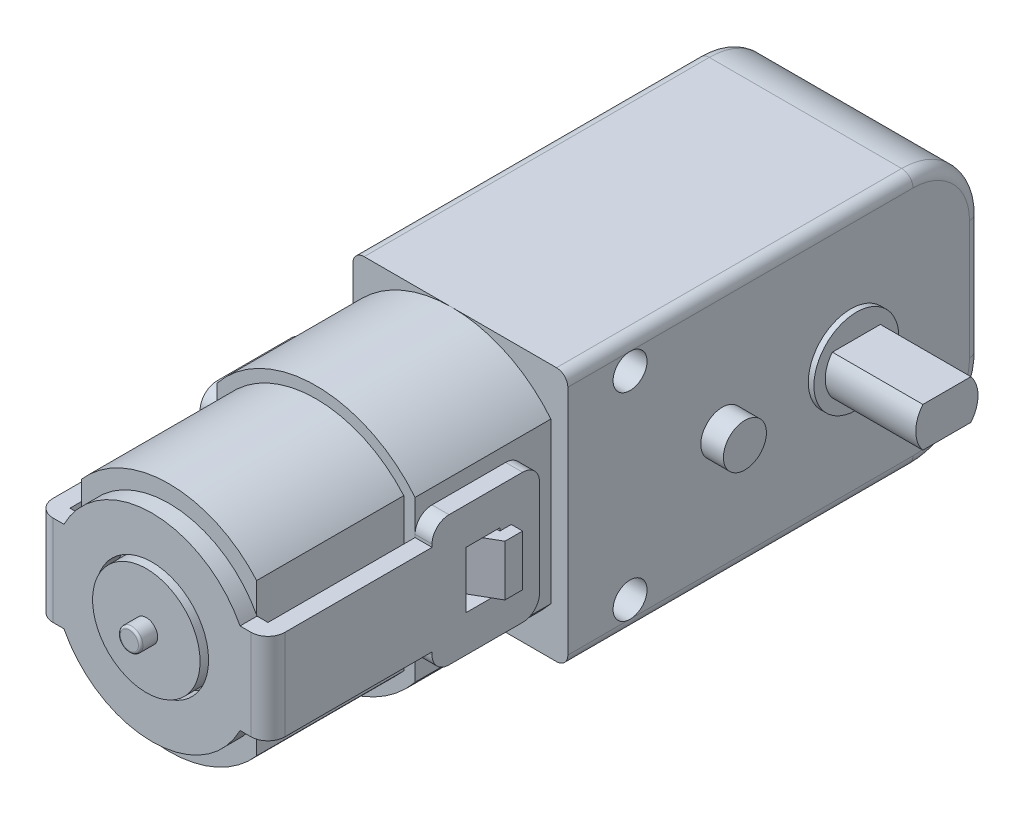
SolidWorks part; units mm, degrees
ref_plane "Plano frontal" through (0, 0, 0) normal (0, 0, 1) x (1, 0, 0)
ref_plane "Plano superior" through (0, 0, 0) normal (0, 1, 0) x (1, 0, 0)
ref_plane "Plano direito" through (0, 0, 0) normal (1, 0, 0) x (0, 0, -1)
sketch "Esboço1" plane through (0, 0, 0) normal (1, 0, 0) x (0, 0, -1)
  line L0 (0, 0) -> (0, 50000) construction
  line L1 (11.5, 11.25) -> (-25, 11.25)
  line L2 (11.5, 11.25) -> (11.5, -11.25)
  line L3 (11.5, -11.25) -> (-25, -11.25)
  line L4 (-25, 11.25) -> (-25, -11.25)
  line L5 (0, 0) -> (50000, 0) construction
  dimension "D1" = 22.5
  dimension "D2" = 11.5
  dimension "D3" = 36.5
extrude "Ressalto-extrusão1" add sketch "Esboço1" along normal mid plane 19
fillet "Filete1" radius 6 2 edges at (0, -11.25, -11.5) (0, 11.25, -11.5)
sketch "Esboço2" plane through (0, 0, 25) normal (0, 0, 1) x (1, 0, 0)
  line L0 (0, 0) -> (0, 50000) construction
  line L1 (0, 0) -> (50000, 0) construction
  line L2 (9.5, -11.25) -> (-9.5, -11.25) construction
  line L3 (9.5, 11.25) -> (-9.5, 11.25) construction
  line L4 (8, 7.0711) -> (8, -7.0711)
  line L5 (-9.5, -7.0711) -> (-9.5, 7.0711)
  line L6 (-9.5, 11.25) -> (-9.5, -11.25) construction
  line L10 (9.5, 11.25) -> (9.5, -11.25) construction
  arc A0 (-9.5, -7.0711) -> (8, -7.0711) centre (-0.75, 0) ccw
  arc A1 (8, 7.0711) -> (-9.5, 7.0711) centre (-0.75, 0) ccw
  dimension "D1" = 1.5
extrude "Ressalto-extrusão2" add sketch "Esboço2" along normal blind 12
sketch "Esboço3" plane through (0, 0, 37) normal (0, 0, 1) x (1, 0, 0)
  line L0 (-8.5, 6.7082) -> (-8.5, -6.7082)
  line L1 (7, -6.7082) -> (7, 6.7082)
  line L2 (-9.5, 7.0711) -> (-9.5, -7.0711)
  line L3 (8, -7.0711) -> (8, 7.0711)
  line L4 (-9.5, 7.0711) -> (-9.5, -7.0711) construction
  line L5 (8, -7.0711) -> (8, 7.0711) construction
  arc A0 (-8.5, -6.7082) -> (7, -6.7082) centre (-0.75, 0) ccw
  arc A1 (7, 6.7082) -> (-8.5, 6.7082) centre (-0.75, 0) ccw
  arc A2 (8, 7.0711) -> (-9.5, 7.0711) centre (-0.75, 0) ccw
  arc A3 (-9.5, -7.0711) -> (8, -7.0711) centre (-0.75, 0) ccw
  arc A4 (8, 7.0711) -> (-9.5, 7.0711) centre (-0.75, 0) ccw construction
  arc A5 (-9.5, -7.0711) -> (8, -7.0711) centre (-0.75, 0) ccw construction
  dimension "D1" = 0
  dimension "D2" = 1
extrude "Ressalto-extrusão3" add sketch "Esboço3" along normal blind 13
sketch "Esboço4" plane through (9.5, 0, 0) normal (1, 0, 0) x (0, 0, -1)
  circle A0 centre (0, 0) radius 3.75
  dimension "D1" = 7.5
extrude "Ressalto-extrusão4" add sketch "Esboço4" along normal blind 0.5
sketch "Esboço5" plane through (8, 0, 0) normal (1, 0, 0) x (0, 0, -1)
  line L0 (-37, -7.0711) -> (-37, 7.0711) construction
  line L1 (-27.5, 5.75) -> (-37, 5.75)
  line L2 (-27.5, 5.75) -> (-27.5, -5.75)
  line L3 (-27.5, -5.75) -> (-37, -5.75)
  line L4 (-37, 5.75) -> (-37, -5.75)
  line L5 (0, 0) -> (-50000, 0) construction
  line L6 (0, 0) -> (0, 50000) construction
  line L7 (-25, 11.25) -> (-25, -11.25) construction
  dimension "D1" = 2.5
  dimension "D2" = 11.5
extrude "Ressalto-extrusão5" add sketch "Esboço5" along normal blind 1.5 separate body
sketch "Esboço6" plane through (0, 0, 37) normal (0, 0, 1) x (1, 0, 0)
  line L0 (9.5, 5.75) -> (9.5, -5.75) construction
  line L1 (9.5, 4) -> (8, 4)
  line L2 (9.5, 4) -> (9.5, -4)
  line L3 (9.5, -4) -> (8, -4)
  line L4 (8, 4) -> (8, -4)
  line L5 (8, -7.0711) -> (8, 7.0711) construction
  line L6 (0, 0) -> (-50000, 0) construction
  dimension "D1" = 8
extrude "Ressalto-extrusão6" add sketch "Esboço6" along normal up to surface (13 mm away) up to face at (-0.75, 0, 50)
sketch "Esboço7" plane through (0, 0, 50) normal (0, 0, 1) x (1, 0, 0)
  line L0 (9.5, 4) -> (7.0322, 4)
  line L1 (9.5, 4) -> (9.5, -4)
  line L2 (9.5, -4) -> (7.0322, -4)
  line L3 (-0.75, 8.75) -> (-0.75, 0) construction
  line L4 (-11, -4) -> (-8.5322, -4)
  line L5 (-11, 4) -> (-11, -4)
  line L6 (-11, 4) -> (-8.5322, 4)
  arc A0 (7.0322, 4) -> (-8.5322, 4) centre (-0.75, 0) ccw
  arc A1 (7, 6.7082) -> (-8.5, 6.7082) centre (-0.75, 0) ccw construction
  arc A2 (-8.5322, -4) -> (7.0322, -4) centre (-0.75, 0) ccw
  circle A3 centre (-0.75, 0) radius 5
  dimension "D1" = 17.5
  dimension "D2" = 10
sketch "Esboço8" plane through (0, 0, 50) normal (0, 0, 1) x (1, 0, 0)
  circle A0 centre (-0.75, 0) radius 4.75
  dimension "D1" = 9.5
extrude "Ressalto-extrusão7" add sketch "Esboço8" along normal blind 2
extrude "Ressalto-extrusão8" add sketch "Esboço7" along normal blind 1.5
ref_plane "Plano1" through (-0.75, 8.75, 51.5) normal (-1, 0, 0) x (0, 0, 1)
sketch "Esboço10" plane through (0, 0, 50) normal (0, 0, -1) x (-1, 0, 0)
  line L0 (11, -4) -> (8.5322, -4) construction
  line L1 (11, 4) -> (9.5, 4)
  line L2 (11, 4) -> (11, -4)
  line L3 (11, -4) -> (9.5, -4)
  line L4 (9.5, 4) -> (9.5, -4)
  line L5 (-9.5, 4) -> (-8, 4) construction
extrude "Ressalto-extrusão9" add sketch "Esboço10" along normal up to surface (13 mm away) up to face at (8.9375, 5.3125, 37)
sketch "Esboço11" plane through (0, 0, 37) normal (0, 0, -1) x (-1, 0, 0)
  line L0 (11, -4) -> (11, 4) construction
  line L1 (11, 5.75) -> (9.5, 5.75)
  line L2 (11, 5.75) -> (11, -5.75)
  line L3 (11, -5.75) -> (9.5, -5.75)
  line L4 (9.5, 5.75) -> (9.5, -5.75)
  line L5 (9.5, 4) -> (9.5, -4) construction
  line L6 (-9.5, -5.75) -> (-9.5, 5.75) construction
  line L7 (-9.5, 5.75) -> (-8, 5.75) construction
extrude "Ressalto-extrusão10" add sketch "Esboço11" along normal up to surface (9.5 mm away) up to face at (8.75, 0, 27.5)
fillet "Filete2" radius 1.5 10 edges at (8.75, -5.75, 37) (8.75, -5.75, 27.5) (8.75, 5.75, 27.5) (8.75, 5.75, 37) (9.5, 0, 51.5) (-11, 0, 51.5) (-10.25, -5.75, 27.5) (-10.25, -5.75, 37) (-10.25, 5.75, 37) (-10.25, 5.75, 27.5)
sketch "Esboço12" plane through (9.5, 0, 0) normal (1, 0, 0) x (0, 0, -1)
  line L0 (-25, 11.25) -> (-25, -11.25) construction
  line L1 (-31, 2.5) -> (-34, 2.5)
  line L2 (-31, 2.5) -> (-31, -2.5)
  line L3 (-31, -2.5) -> (-34, -2.5)
  line L4 (-34, 2.5) -> (-34, -2.5)
  line L5 (0, 0) -> (-50000, 0) construction
  dimension "D1" = 6
  dimension "D2" = 3
  dimension "D3" = 5
extrude "Corte-extrusão1" cut sketch "Esboço12" against normal through all
sketch "Esboço14" plane through (0, 0, 0) normal (0, 1, 0) x (1, 0, 0)
  line L0 (8, -33) -> (10.5, -31.5566)
  line L1 (8, -37) -> (8, -25) construction
  line L2 (10.5, -31.5566) -> (10.5, -30)
  line L3 (10.5, -30) -> (9.5, -30)
  line L4 (9.5, -35.5) -> (9.5, -29) construction
  line L5 (9.5, -30) -> (9.5, -31)
  line L6 (8, -31) -> (9.5, -31) construction
  line L7 (9.5, -31) -> (8, -31)
  line L8 (8, -31) -> (8, -33)
  dimension "D1" = 2.5
  dimension "D2" = 1
  dimension "D3" = 60
  dimension "D4" = 2
extrude "Ressalto-extrusão11" add sketch "Esboço14" along normal mid plane 4.5
mirror "Espelhar6" about plane through (-0.75, 8.75, 51.5) normal (-1, 0, 0) of "Ressalto-extrusão11"
sketch "Esboço15" plane through (0, 0, 52) normal (0, 0, 1) x (1, 0, 0)
  circle A0 centre (-0.75, 0) radius 1
  dimension "D1" = 2
extrude "Ressalto-extrusão12" add sketch "Esboço15" along normal blind 1.5
sketch "Esboço16" plane through (10, 0, 0) normal (1, 0, 0) x (0, 0, -1)
  line L0 (0, 0) -> (-50000, 0) construction
  line L1 (-2.1213, 1.75) -> (2.1213, 1.75)
  line L3 (2.1213, -1.75) -> (-2.1213, -1.75)
  arc A0 (2.1213, -1.75) -> (2.1213, 1.75) centre (0, 0) ccw
  arc A1 (-2.1213, 1.75) -> (-2.1213, -1.75) centre (0, 0) ccw
  dimension "D1" = 5.5
  dimension "D2" = 3.5
extrude "Ressalto-extrusão13" add sketch "Esboço16" along normal blind 8
fillet "Filete4" radius 1 10 edges at (-9.5, -11.25, 9.75) (-9.5, -9.4926, -9.7426) (-9.5, 0, -11.5) (-9.5, 9.4926, -9.7426) (9.5, -11.25, 9.75) (9.5, -9.4926, -9.7426) (9.5, 0, -11.5) (9.5, 9.4926, -9.7426) (-9.5, 11.25, 9.75) (9.5, 11.25, 9.75)
sketch "Esboço17" plane through (9.5, 0, 0) normal (1, 0, 0) x (0, 0, -1)
  line L0 (-19.5, 8.75) -> (-19.5, -8.75) construction
  line L1 (-19.5, 0) -> (0, 0) construction
  line L2 (-25, 11.25) -> (-25, 7.0711) construction
  circle A0 centre (-19.5, 8.75) radius 1.5
  circle A1 centre (-19.5, -8.75) radius 1.5
  dimension "D2" = 3
  dimension "D3" = 4
  dimension "D1" = 17.5
extrude "Corte-extrusão2" cut sketch "Esboço17" against normal through all
sketch "Esboço19" plane through (0, 0, 0) normal (1, 0, 0) x (0, 0, -1)
  line L0 (11.5, 3) -> (14.4508, 2.459)
  line L1 (11.5, 5.25) -> (11.5, -5.25) construction
  line L2 (14.4508, -2.459) -> (11.5, -3)
  line L3 (11.5, -3) -> (11.5, 3)
  line L4 (0, 0) -> (50000, 0) construction
  arc A0 (14.4508, 2.459) -> (14.4508, -2.459) centre (14, 0) cw
  circle A1 centre (14, 0) radius 1.5
  dimension "D2" = 5
  dimension "D3" = 3
  dimension "D4" = 2.5
  dimension "D1" = 6
extrude "Ressalto-extrusão14" add sketch "Esboço19" along normal mid plane 3
fillet "Filete5" radius 1 2 edges at (0, 3, -11.5) (0, -3, -11.5)
fillet "Filete6" radius 0.2 1 edges at (0.25, 0, 53.5)
sketch "Sketch3" plane through (9.5, 0, 0) normal (1, 0, 0) x (0, 0, -1)
  line L0 (0, 0) -> (-27.5, 0) construction
  line L1 (-27.5, -4.25) -> (-27.5, 4.25) construction
  circle A0 centre (-11.35, 0) radius 1.9
  arc A2 (-2.1213, 1.75) -> (-2.1213, -1.75) centre (0, 0) ccw construction
  point P7 (-2.75, 0)
  point P10 (-9.45, 0)
  dimension "D1" = 3.8
  dimension "D2" = 6.7
extrude "Boss-Extrude1" add sketch "Sketch3" along normal blind 2
mirror "Mirror1" about plane through (0, 0, 0) normal (1, 0, 0) of "Ressalto-extrusão13", "Ressalto-extrusão4"
